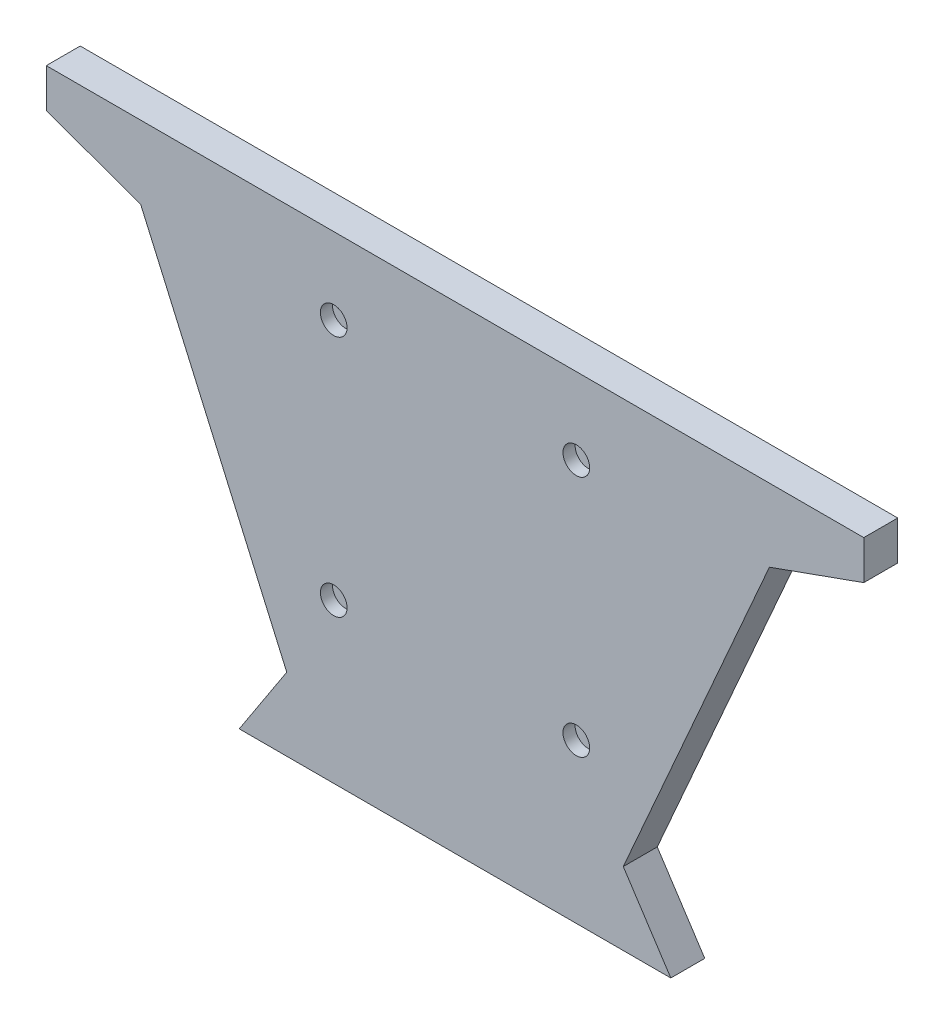
SolidWorks part; units mm, degrees
ref_plane "Front Plane" through (0, 0, 0) normal (0, 0, 1) x (1, 0, 0)
ref_plane "Top Plane" through (0, 0, 0) normal (0, 1, 0) x (1, 0, 0)
ref_plane "Right Plane" through (0, 0, 0) normal (1, 0, 0) x (0, 0, -1)
sketch "Sketch1" plane through (0, 0, 0) normal (0, 0, 1) x (1, 0, 0)
  line L0 (-44.9631, -50) -> (44.9631, -50)
  line L1 (44.9631, -50) -> (85, 41.0508)
  line L2 (85, 41.0508) -> (85, 50)
  line L3 (85, 50) -> (-85, 50)
  line L6 (-85, 50) -> (-85, 41.0508)
  line L7 (-85, 41.0508) -> (-44.9631, -50)
  line L8 (-84.25, 41.2084) -> (-44.4735, -49.25)
  line L9 (-44.4735, -49.25) -> (44.4735, -49.25)
  line L10 (44.4735, -49.25) -> (84.25, 41.2084)
  line L11 (84.25, 41.2084) -> (84.25, 49.25)
  line L12 (84.25, 49.25) -> (-84.25, 49.25)
  line L13 (-84.25, 49.25) -> (-84.25, 41.2084)
  dimension "D1" = 0.75
extrude "Boss-Extrude1" add sketch "Sketch1" along normal blind 7 contours L8 L9 L10 L11 L12 L13
sketch "Sketch2" plane through (0, 0, 0) normal (0, 0, -1) x (-1, 0, 0)
  line L6 (-34.6832, -34.25) -> (-44.4735, -49.25)
  line L7 (-44.4735, -49.25) -> (-84.25, 41.2084)
  line L8 (-84.25, 41.2084) -> (-64.8041, 34.25)
  line L9 (64.8041, 34.25) -> (84.25, 41.2084)
  line L10 (84.25, 41.2084) -> (44.4735, -49.25) construction
  line L11 (84.25, 41.2084) -> (44.4735, -49.25)
  line L12 (64.8041, 34.25) -> (-64.8041, 34.25)
  line L13 (-64.8041, 34.25) -> (-34.6832, -34.25)
  line L14 (-34.6832, -34.25) -> (34.6832, -34.25)
  line L15 (34.6832, -34.25) -> (64.8041, 34.25)
  line L16 (64.8041, 34.25) -> (-64.8041, 34.25)
  line L17 (-64.8041, 34.25) -> (-34.6832, -34.25)
  line L18 (-34.6832, -34.25) -> (34.6832, -34.25)
  line L19 (34.6832, -34.25) -> (64.8041, 34.25)
  line L20 (44.4735, -49.25) -> (34.6832, -34.25)
  line M8 (-84.25, 41.2084) -> (-44.4735, -49.25)
  line M10 (44.4735, -49.25) -> (84.25, 41.2084)
  dimension "D1" = 15
extrude "Cut-Extrude1" cut sketch "Sketch2" against normal blind 10 contours L20 L9 L19 M10 | L17 L8 L6 M8
sketch "Sketch3" plane through (0, 0, 7) normal (0, 0, 1) x (1, 0, 0)
  line L1 (-25, -16.5531) -> (25, -16.5531)
  line L2 (-25, -16.5531) -> (-25, 33.4469)
  line L3 (-25, 33.4469) -> (25, 33.4469)
  line L4 (25, -16.5531) -> (25, 33.4469)
  line L5 (-25, -16.5531) -> (25, 33.4469) construction
  line L6 (-25, 33.4469) -> (25, -16.5531) construction
  circle A0 centre (25, 33.4469) radius 2.75
  circle A1 centre (-25, 33.4469) radius 2.75
  circle A2 centre (-25, -16.5531) radius 2.75
  circle A3 centre (25, -16.5531) radius 2.75
  point P0 (0, 8.4469)
  dimension "D4" = 5.5
  dimension "D1" = 50
  dimension "D2" = 50
  dimension "D3" = 0
  dimension "D5" = 2
  dimension "D6" = 2
extrude "Cut-Extrude2" cut sketch "Sketch3" against normal blind 2.5 contours A1 | A0 | A3 | A2
ref_plane "Plane1" through (0, 0, 3.5) normal (0, 0, -1) x (-1, 0, 0)
mirror "Mirror1" about plane through (0, 0, 3.5) normal (0, 0, -1) of "Cut-Extrude2"
